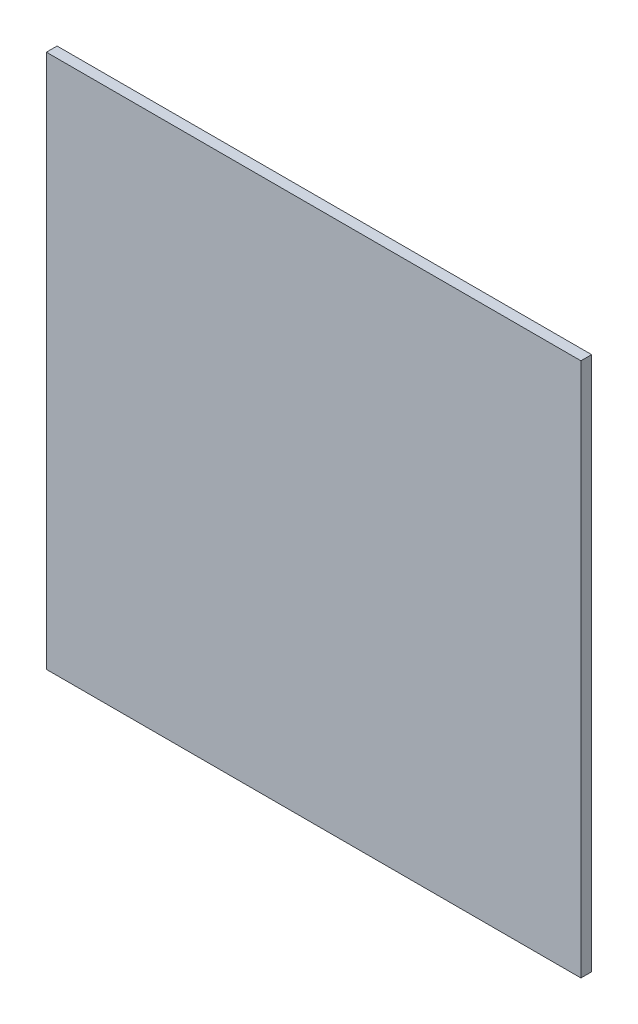
SolidWorks part; units mm, degrees
ref_plane "Plan de face" through (0, 0, 0) normal (0, 0, 1) x (1, 0, 0)
ref_plane "Plan de dessus" through (0, 0, 0) normal (0, 1, 0) x (1, 0, 0)
ref_plane "Plan de droite" through (0, 0, 0) normal (1, 0, 0) x (0, 0, -1)
sketch "Esquisse1" plane through (0, 0, 0) normal (0, 0, 1) x (1, 0, 0)
  line L1 (-713.7902, 371.4953) -> (-213.7902, 371.4953)
  line L2 (-713.7902, 371.4953) -> (-713.7902, -128.5047)
  line L3 (-713.7902, -128.5047) -> (-213.7902, -128.5047)
  line L4 (-213.7902, 371.4953) -> (-213.7902, -128.5047)
  line L5 (-713.7902, 371.4953) -> (-213.7902, -128.5047) construction
  line L6 (-713.7902, -128.5047) -> (-213.7902, 371.4953) construction
  point P0 (-463.7902, 121.4953)
  dimension "D1" = 500
  dimension "D2" = 500
extrude "Boss.-Extru.1" add sketch "Esquisse1" along normal blind 10
